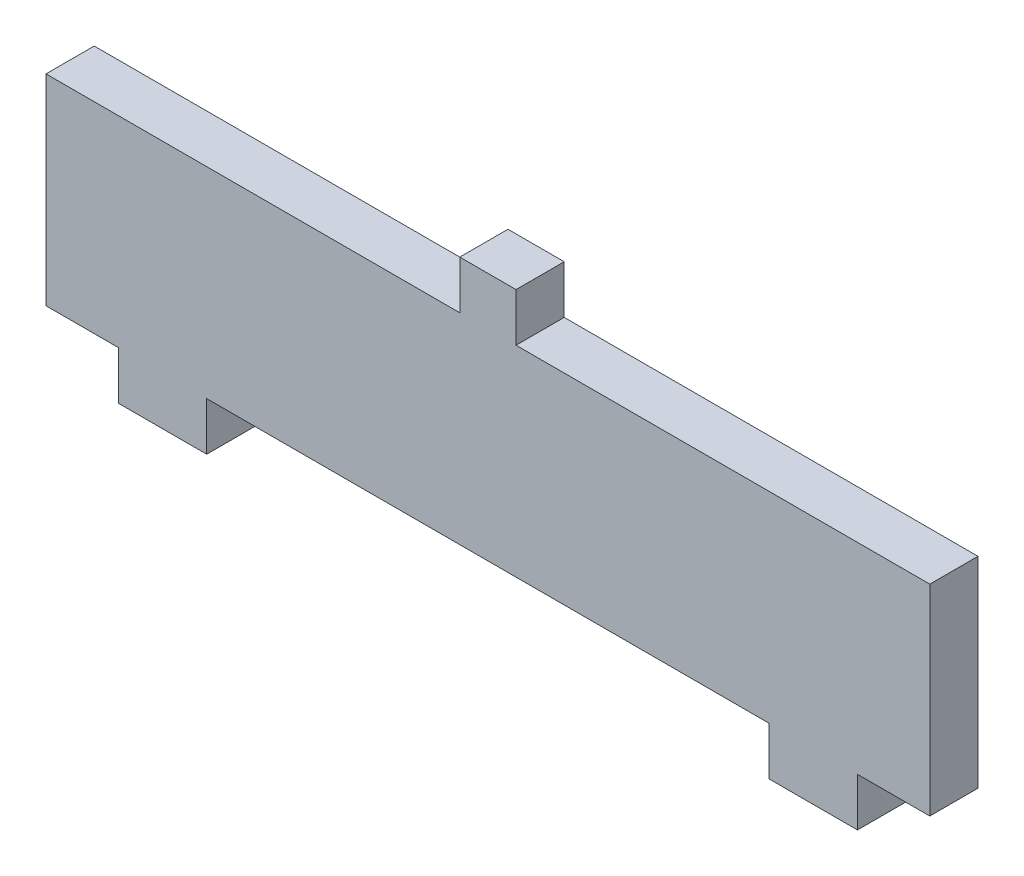
SolidWorks part; units mm, degrees
ref_plane "Alzado" through (0, 0, 0) normal (0, 0, 1) x (1, 0, 0)
ref_plane "Planta" through (0, 0, 0) normal (0, 1, 0) x (1, 0, 0)
ref_plane "Vista lateral" through (0, 0, 0) normal (1, 0, 0) x (0, 0, -1)
sketch "Croquis1" plane through (0, 0, 0) normal (0, 0, 1) x (1, 0, 0)
  line L0 (1.75, 6.25) -> (27.5, 6.25)
  line L1 (-27.5, -6.25) -> (-23, -6.25)
  line L2 (-27.5, -6.25) -> (-27.5, 6.25)
  line L3 (-27.5, 6.25) -> (-1.75, 6.25)
  line L4 (27.5, -6.25) -> (27.5, 6.25)
  line L5 (-27.5, -6.25) -> (27.5, 6.25) construction
  line L6 (-27.5, 6.25) -> (27.5, -6.25) construction
  line L7 (-17.5, -6.25) -> (17.5, -6.25)
  line L8 (-1.75, 6.25) -> (-1.75, 9.25)
  line L9 (-1.75, 9.25) -> (1.75, 9.25)
  line L10 (1.75, 6.25) -> (1.75, 9.25)
  line L11 (23, -6.25) -> (27.5, -6.25)
  line L12 (-23, -6.25) -> (-23, -9.25)
  line L13 (-23, -9.25) -> (-17.5, -9.25)
  line L14 (-17.5, -6.25) -> (-17.5, -9.25)
  line L16 (17.5, -6.25) -> (17.5, -9.25)
  line L17 (17.5, -9.25) -> (23, -9.25)
  line L18 (23, -6.25) -> (23, -9.25)
  point P0 (0, 0)
  point P18 (0, 9.25)
  dimension "D1" = 55
  dimension "D2" = 12.5
  dimension "D3" = 3
  dimension "D4" = 3
  dimension "D5" = 5.5
  dimension "D6" = 5.5
  dimension "D7" = 3.5
  dimension "D8" = 4.5
  dimension "D9" = 35
extrude "Saliente-Extruir1" add sketch "Croquis1" along normal blind 3
